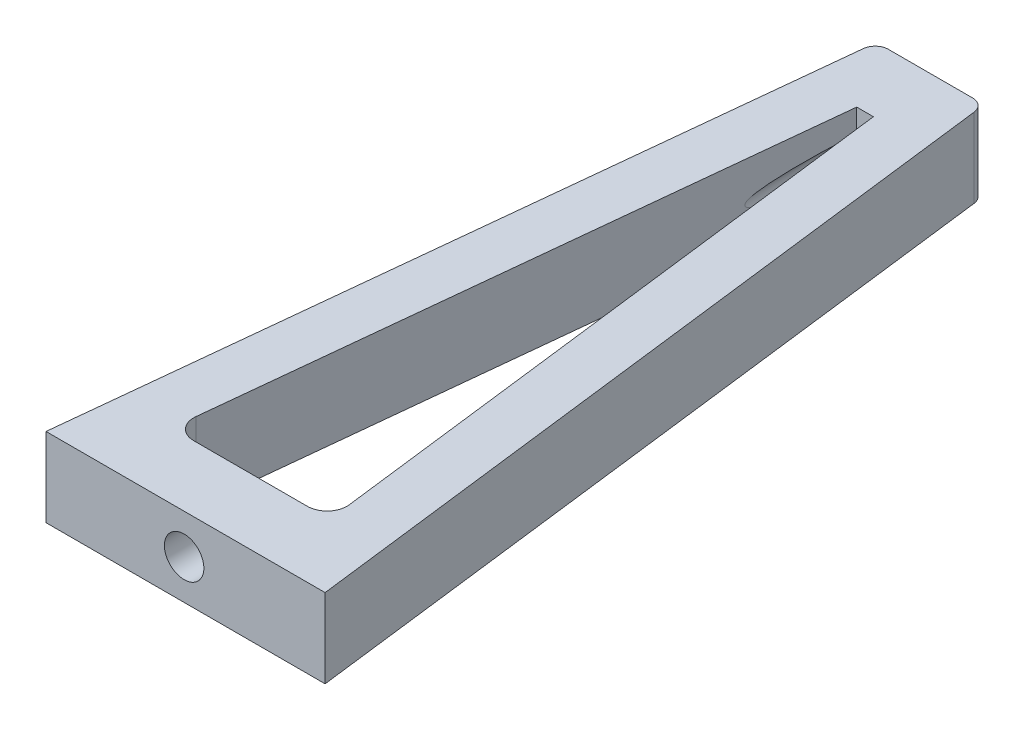
SolidWorks part; units mm, degrees
ref_plane "Front Plane" through (0, 0, 0) normal (0, 0, 1) x (1, 0, 0)
ref_plane "Top Plane" through (0, 0, 0) normal (0, 1, 0) x (1, 0, 0)
ref_plane "Right Plane" through (0, 0, 0) normal (1, 0, 0) x (0, 0, -1)
sketch "Sketch1" plane through (0, 0, 0) normal (0, 1, 0) x (1, 0, 0)
  line L0 (13.1953, 46.2263) -> (18.7733, 1.1227) construction
  line L2 (9.6747, 42.1036) -> (15.2917, -3.3159)
  line L3 (5.8079, 47.1036) -> (12.2029, 47.1036)
  line L4 (13.1953, 46.2263) -> (20.1488, -10)
  line L5 (4.8133, 46.2072) -> (-1.0417, -10)
  line L6 (4.8133, 46.2072) -> (0.115, 1.1036) construction
  line L7 (8.4074, 42.1036) -> (3.6732, -3.3446)
  line L8 (20.1488, -10) -> (-1.0417, -10)
  line L9 (9.6747, 42.1036) -> (8.4074, 42.1036)
  line L10 (8.5116, 43.1036) -> (4.4383, 4) construction
  line L11 (9.551, 43.1036) -> (14.387, 4) construction
  line L12 (8.5116, 43.1036) -> (9.551, 43.1036) construction
  line L13 (4.4383, 4) -> (14.387, 4) construction
  line L15 (1.1096, 0) -> (17.7808, 0) construction
  line L16 (5.1652, -5) -> (13.8031, -5)
  arc A0 (13.8031, -5) -> (15.2917, -3.3159) centre (13.8031, -3.5) ccw
  arc A1 (3.6732, -3.3446) -> (5.1652, -5) centre (5.1652, -3.5) ccw
  arc A2 (12.2029, 47.1036) -> (13.1953, 46.2263) centre (12.2029, 46.1036) cw
  arc A3 (5.8079, 47.1036) -> (4.8133, 46.2072) centre (5.8079, 46.1036) ccw
  arc A9 (9.551, 43.1036) -> (9.551, 43.1036) centre (9.551, 43.1036) cw construction
  arc A10 (8.5116, 43.1036) -> (8.5116, 43.1036) centre (8.5116, 43.1036) ccw construction
  arc A11 (14.387, 4) -> (14.387, 4) centre (14.387, 4) ccw construction
  arc A12 (4.4383, 4) -> (4.4383, 4) centre (4.4383, 4) cw construction
  arc A13 (1.1096, 0) -> (0.115, 1.1036) centre (1.1096, 1) cw construction
  arc A14 (17.7808, 0) -> (18.7733, 1.1227) centre (17.7808, 1) ccw construction
  point P9 (0, 0)
extrude "Boss-Extrude1" add sketch "Sketch1" along normal blind 6
sketch "Sketch3" plane through (0, 0, -47.1036) normal (0, 0, -1) x (-1, 0, 0)
  circle A0 centre (-9.0054, 3) radius 1.4
extrude "Cut-Extrude1" cut sketch "Sketch3" against normal blind 20
sketch "Sketch4" plane through (0, 0, 0) normal (0, 0, 1) x (1, 0, 0)
  circle A0 centre (9.4452, 3) radius 1.5
extrude "Cut-Extrude2" cut sketch "Sketch4" along normal blind 200
